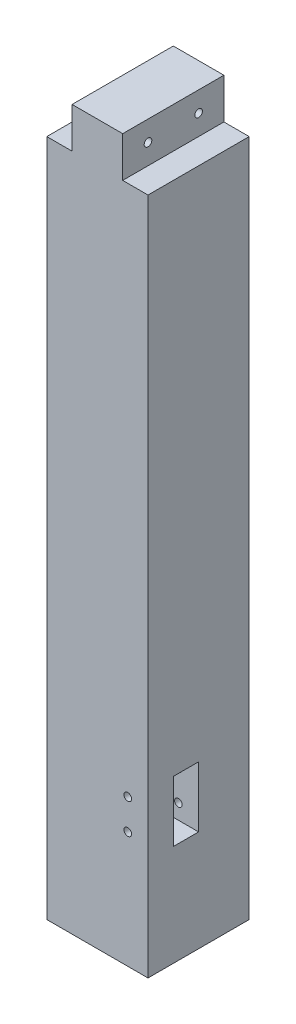
SolidWorks part; units mm, degrees
material "Pine"
ref_plane "Front Plane" through (0, 0, 0) normal (0, 0, 1) x (1, 0, 0)
ref_plane "Top Plane" through (0, 0, 0) normal (0, 1, 0) x (1, 0, 0)
ref_plane "Right Plane" through (0, 0, 0) normal (1, 0, 0) x (0, 0, -1)
sketch "Sketch1" plane through (0, 0, 0) normal (0, 0, 1) x (1, 0, 0)
  line L0 (0, 0) -> (0, 50000) construction
  line L1 (63.5, 425.45) -> (-63.5, 425.45)
  line L2 (63.5, 425.45) -> (63.5, -425.45)
  line L3 (63.5, -425.45) -> (-63.5, -425.45)
  line L4 (-63.5, 425.45) -> (-63.5, -425.45)
  line L5 (63.5, 425.45) -> (-63.5, -425.45) construction
  line L6 (63.5, -425.45) -> (-63.5, 425.45) construction
  line L8 (-31.75, 476.25) -> (31.75, 476.25)
  line L9 (-31.75, 476.25) -> (-31.75, 374.65)
  line L10 (-31.75, 374.65) -> (31.75, 374.65)
  line L11 (31.75, 476.25) -> (31.75, 374.65)
  line L12 (-31.75, 476.25) -> (31.75, 374.65) construction
  line L13 (-31.75, 374.65) -> (31.75, 476.25) construction
  point P0 (0, 0)
  point P8 (0, 425.45)
  dimension "D1" = 850.9
  dimension "D2" = 127
  dimension "D3" = 63.5
  dimension "D4" = 101.6
extrude "Boss-Extrude1" add sketch "Sketch1" along normal blind 127 contours L1 L11 L10 L9 L4 L3 L2 | L11 L1 L9 L10 | L11 L8 L9 L1
sketch "Sketch2" plane through (63.5, 0, 0) normal (1, 0, 0) x (0, 0, -1)
  line L0 (-127, 425.45) -> (-127, -425.45) construction
  line L1 (-63.5, -222.25) -> (-95.25, -222.25)
  line L2 (-63.5, -222.25) -> (-63.5, -298.45)
  line L3 (-63.5, -298.45) -> (-95.25, -298.45)
  line L4 (-95.25, -222.25) -> (-95.25, -298.45)
  line L5 (-63.5, -222.25) -> (-95.25, -298.45) construction
  line L6 (-63.5, -298.45) -> (-95.25, -222.25) construction
  line L7 (-127, -425.45) -> (0, -425.45) construction
  point P0 (-79.375, -260.35)
  point P5 (-79.375, -222.25)
  dimension "D1" = 76.2
  dimension "D2" = 31.75
  dimension "D3" = 31.75
  dimension "D4" = 127
extrude "Cut-Extrude1" cut sketch "Sketch2" against normal blind 50.8
sketch "Sketch3" plane through (0, 0, 127) normal (0, 0, 1) x (1, 0, 0)
  line L0 (38.1, -222.25) -> (38.1, -298.45) construction
  line L4 (63.5, -298.45) -> (63.5, -222.25)
  line L5 (12.7, -298.45) -> (63.5, -298.45)
  line L6 (12.7, -222.25) -> (12.7, -298.45)
  line L7 (63.5, -222.25) -> (12.7, -222.25)
  line L8 (63.5, -298.45) -> (63.5, -222.25)
  line L9 (12.7, -298.45) -> (63.5, -298.45)
  line L10 (12.7, -222.25) -> (12.7, -298.45)
  line L11 (63.5, -222.25) -> (12.7, -222.25)
  circle A0 centre (38.1, -279.4) radius 4.7625
  circle A1 centre (38.1, -241.3) radius 4.7625
  point P10 (38.1, -260.35)
  dimension "D2" = 9.525
  dimension "D3" = 19.05
  dimension "D4" = 19.05
  dimension "D1" = 0
extrude "Cut-Extrude3" cut sketch "Sketch3" against normal blind 82.55 contours A0 L0 | L0 A0 | L0 A1 | A1 L0
sketch "Sketch4" plane through (0, 0, 0) normal (0, 0, -1) x (-1, 0, 0)
  line L0 (63.5, 425.45) -> (63.5, -425.45) construction
  line L1 (31.75, -222.25) -> (0, -222.25)
  line L2 (31.75, -222.25) -> (31.75, -298.45)
  line L3 (31.75, -298.45) -> (0, -298.45)
  line L4 (0, -222.25) -> (0, -298.45)
  line L5 (31.75, -222.25) -> (0, -298.45) construction
  line L6 (31.75, -298.45) -> (0, -222.25) construction
  line L7 (-63.5, -425.45) -> (63.5, -425.45) construction
  point P0 (15.875, -260.35)
  dimension "D1" = 31.75
  dimension "D2" = 76.2
  dimension "D3" = 31.75
  dimension "D4" = 127
extrude "Cut-Extrude4" cut sketch "Sketch4" against normal blind 63.5
sketch "Sketch5" plane through (-63.5, 0, 0) normal (-1, 0, 0) x (0, 0, 1)
  line L0 (31.75, -298.45) -> (31.75, -222.25) construction
  line L4 (0, -222.25) -> (0, -298.45)
  line L5 (0, -298.45) -> (63.5, -298.45)
  line L6 (63.5, -298.45) -> (63.5, -222.25)
  line L7 (63.5, -222.25) -> (0, -222.25)
  line L8 (0, -222.25) -> (0, -298.45)
  line L9 (0, -298.45) -> (63.5, -298.45)
  line L10 (63.5, -298.45) -> (63.5, -222.25)
  line L11 (63.5, -222.25) -> (0, -222.25)
  circle A0 centre (31.75, -241.3) radius 4.7625
  circle A1 centre (31.75, -279.4) radius 4.7625
  point P10 (31.75, -260.35)
  dimension "D5" = 9.525
  dimension "D2" = 31.75
  dimension "D3" = 19.05
  dimension "D4" = 19.05
  dimension "D1" = 0
extrude "Cut-Extrude5" cut sketch "Sketch5" against normal blind 76.2 contours L0 A0 | A0 L0 | L0 A1 | A1 L0
sketch "Sketch6" plane through (31.75, 0, 0) normal (1, 0, 0) x (0, 0, -1)
  line L0 (-127, 450.85) -> (0, 450.85) construction
  line L1 (-127, 476.25) -> (-127, 425.45) construction
  line L2 (0, 476.25) -> (0, 425.45) construction
  circle A0 centre (-95.25, 450.85) radius 4.7625
  circle A1 centre (-31.75, 450.85) radius 4.7625
  point P10 (-63.5, 450.85)
  dimension "D3" = 9.525
  dimension "D1" = 31.75
  dimension "D2" = 31.75
extrude "Cut-Extrude6" cut sketch "Sketch6" against normal through all
